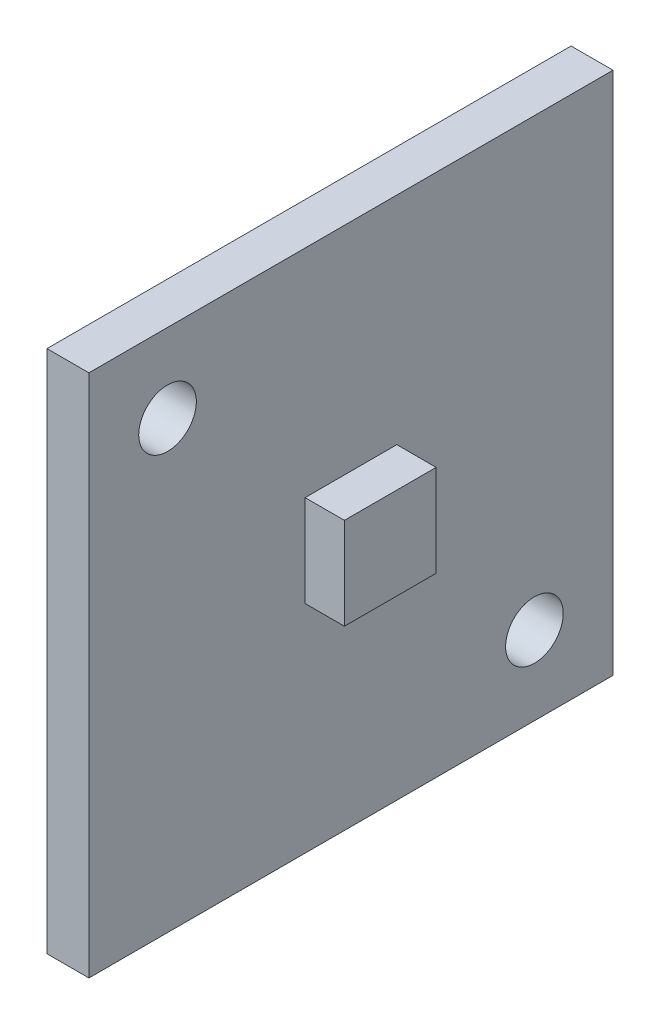
SolidWorks part; units mm, degrees
ref_plane "Front Plane" through (0, 0, 0) normal (0, 0, 1) x (1, 0, 0)
ref_plane "Top Plane" through (0, 0, 0) normal (0, 1, 0) x (1, 0, 0)
ref_plane "Right Plane" through (0, 0, 0) normal (1, 0, 0) x (0, 0, -1)
other "Configuration Table"
sketch "Sketch1" plane through (0, 0, 0) normal (1, 0, 0) x (0, 0, -1)
  line L1 (-10, -10) -> (10, -10)
  line L2 (-10, -10) -> (-10, 10)
  line L3 (-10, 10) -> (10, 10)
  line L4 (10, -10) -> (10, 10)
  line L5 (-10, -10) -> (10, 10) construction
  line L6 (-10, 10) -> (10, -10) construction
  point P6 (0, 0)
  dimension "D1" = 20
  dimension "D2" = 20
extrude "Board" add sketch "Sketch1" against normal blind 1.6
sketch "Sketch2" plane through (0, 0, 0) normal (1, 0, 0) x (0, 0, -1)
  line L0 (-1.75, -1.75) -> (1.75, -1.75)
  line L1 (1.75, -1.75) -> (1.75, 1.75)
  line L2 (1.75, 1.75) -> (-1.75, 1.75)
  line L3 (-1.75, 1.75) -> (-1.75, -1.75)
extrude "UV_LED_3535" add sketch "Sketch2" along normal blind 1.5
sketch "Sketch3" plane through (0, 0, 0) normal (1, 0, 0) x (0, 0, -1)
  circle A0 centre (7, -7) radius 1.1
  circle A1 centre (-7, 7) radius 1.1
  dimension "D1" = 2.2
  dimension "D2" = 2.2
extrude "Holes_M2" cut sketch "Sketch3" along normal through all and the other way through all
equation "\"Jar_OD\"= 90  'ASSUMED - Part G fallback - jar outer diameter"
equation "\"Jar_H\"= 120  'ASSUMED - Part G fallback - jar height"
equation "\"Pump_L\"= 45  'ASSUMED - Part G fallback"
equation "\"Pump_W\"= 24  'ASSUMED - Part G fallback"
equation "\"Pump_H\"= 33  'ASSUMED - Part G fallback"
equation "\"Pump_Outlet_OD\"= 7.5  'ASSUMED - Part G fallback"
equation "\"Tube_OD\"= 8  'ASSUMED - Part G fallback"
equation "\"Tube_ID\"= 6  'ASSUMED - Part G fallback"
equation "\"TDS_Body_Dia\"= 12  'ASSUMED - Part G fallback"
equation "\"TDS_Wet_Len\"= 45  'ASSUMED - Part G fallback - length in water"
equation "\"DS_Tube_Dia\"= 6  'ASSUMED - Part G fallback"
equation "\"DS_Tube_Len\"= 50  'ASSUMED - Part G fallback"
equation "\"ORP_Body_Dia\"= 12  'ASSUMED - Part G fallback"
equation "\"ORP_Body_Len\"= 150  'ASSUMED - Part G fallback"
equation "\"ORP_Cap_Dia\"= 16  'ASSUMED - Part G fallback"
equation "\"Turb_W\"= 33  'ASSUMED - Part G fallback - head width"
equation "\"Turb_D\"= 28  'ASSUMED - Part G fallback - head depth"
equation "\"Turb_H\"= 30  'ASSUMED - Part G fallback - head height"
equation "\"Turb_Slot_W\"= 10  'ASSUMED - Part G fallback - slot width"
equation "\"Flow_L\"= 62  'ASSUMED - Part G fallback YF-S201"
equation "\"Flow_W\"= 36  'ASSUMED - Part G fallback"
equation "\"Flow_H\"= 35  'ASSUMED - Part G fallback"
equation "\"Thread_G12_OD\"= 20.955  'ASSUMED - Part G fallback thread G1/2 (major diameter)"
equation "\"Valve_L\"= 75  'ASSUMED - Part G fallback"
equation "\"Valve_W\"= 45  'ASSUMED - Part G fallback"
equation "\"Valve_H\"= 60  'ASSUMED - Part G fallback"
equation "\"Tee_L\"= 40  'ASSUMED - Part G fallback - overall length"
equation "\"Tee_Branch_L\"= 25  'ASSUMED - Part G fallback"
equation "\"Tee_OD\"= 12  'ASSUMED - Part G fallback"
equation "\"Cuv_W\"= 12.5  'ASSUMED - old R3 cuvette (station suppressed in SS4)"
equation "\"Cuv_D\"= 12.5  'ASSUMED - old R3 cuvette (station suppressed in SS4)"
equation "\"Cuv_H\"= 45  'ASSUMED - old R3 cuvette (station suppressed in SS4)"
equation "\"LED_Board_L\"= 20  'ASSUMED - Part G fallback"
equation "\"LED_Board_W\"= 20  'ASSUMED - Part G fallback - LED at centre"
equation "\"GUVA_L\"= 20  'ASSUMED - Part G fallback"
equation "\"GUVA_W\"= 12  'ASSUMED - Part G fallback - sensor at centre"
equation "\"Reed_L\"= 27  'ASSUMED - Part G fallback MC-38 half"
equation "\"Reed_W\"= 14  'ASSUMED - Part G fallback"
equation "\"Reed_H\"= 8  'ASSUMED - Part G fallback"
equation "\"ESP_L\"= 51  'ASSUMED - Part G fallback"
equation "\"ESP_W\"= 28  'ASSUMED - Part G fallback"
equation "\"TFT_L\"= 58  'ASSUMED - Part G fallback - board"
equation "\"TFT_W\"= 35  'ASSUMED - Part G fallback - board"
equation "\"TFT_Win_L\"= 35  'ASSUMED - Part G fallback - visible window"
equation "\"TFT_Win_W\"= 28  'ASSUMED - Part G fallback - visible window"
equation "\"Relay_L\"= 50  'ASSUMED - Part G fallback"
equation "\"Relay_W\"= 26  'ASSUMED - Part G fallback"
equation "\"Relay_H\"= 19  'ASSUMED - Part G fallback"
equation "\"Mosfet_L\"= 34  'ASSUMED - Part G fallback"
equation "\"Mosfet_W\"= 17  'ASSUMED - Part G fallback"
equation "\"Mosfet_H\"= 12  'ASSUMED - Part G fallback"
equation "\"TDS_Board_L\"= 42  'ASSUMED - Part G fallback"
equation "\"TDS_Board_W\"= 32  'ASSUMED - Part G fallback"
equation "\"Turb_Board_L\"= 38  'ASSUMED - Part G fallback"
equation "\"Turb_Board_W\"= 28  'ASSUMED - Part G fallback"
equation "\"BNC_Thread_Dia\"= 9.5  'ASSUMED - Part G fallback"
equation "\"Plate_L\"= 420  'ASSUMED - Part G fallback"
equation "\"Plate_W\"= 297  'ASSUMED - Part G fallback"
equation "\"Plate_T\"= 6  'ASSUMED - Part G fallback"
equation "\"Probe_Clr\"= 0.3  'DESIGN VALUE - Part C rule 3 - printed probe hole = diameter + 0.3"
equation "\"Cuv_Clr\"= 0.2  'DESIGN VALUE - Part C rule 3 - cuvette pocket = size + 0.2"
equation "\"Label_H\"= 0.6  'DESIGN VALUE - Part D - raised label height"
equation "\"D1@Sketch1\" = \"LED_Board_W\""
equation "\"D2@Sketch1\" = \"LED_Board_L\""
equation "\"Booster_L\"= 150  'ASSUMED - Part G fallback - booster pump"
equation "\"Booster_W\"= 95  'ASSUMED - Part G fallback"
equation "\"Booster_H\"= 100  'ASSUMED - Part G fallback"
equation "\"PTube_OD\"= 6.35  'ASSUMED - Part G fallback - product tube 1/4 inch"
equation "\"Qz_Out\"= 12  'ASSUMED - Part G fallback - quartz channel outside square"
equation "\"Qz_Path\"= 10  'ASSUMED - Part G fallback - quartz channel inside light path"
equation "\"Qz_L\"= 40  'ASSUMED - Part G fallback - quartz channel length"
equation "\"LED860_Dia\"= 5  'ASSUMED - Part G fallback - 860 nm LED"
equation "\"BPW_L\"= 5.4  'ASSUMED - Part G fallback - BPW34"
equation "\"BPW_W\"= 4.3  'ASSUMED - Part G fallback - BPW34"
equation "\"Cart_Dia\"= 50  'ASSUMED - Part G fallback - sediment and pre-carbon cartridges"
equation "\"Cart_L\"= 255  'ASSUMED - Part G fallback"
equation "\"UF_Dia\"= 50  'ASSUMED - Part G fallback - UF cartridge"
equation "\"UF_L\"= 260  'ASSUMED - Part G fallback"
equation "\"RO_Dia\"= 62  'ASSUMED - Part G fallback - RO membrane housing"
equation "\"RO_L\"= 300  'ASSUMED - Part G fallback"
equation "\"UVC_Dia\"= 40  'ASSUMED - Part G fallback - UV-C chamber"
equation "\"UVC_L\"= 300  'ASSUMED - Part G fallback"
equation "\"Tank_W\"= 260  'ASSUMED - Part G fallback - storage tank"
equation "\"Tank_D\"= 160  'ASSUMED - Part G fallback"
equation "\"Tank_H\"= 300  'ASSUMED - Part G fallback"
equation "\"Cab_W\"= 400  'ASSUMED - Part G fallback - purifier cabinet"
equation "\"Cab_D\"= 270  'ASSUMED - Part G fallback"
equation "\"Cab_H\"= 560  'ASSUMED - Part G fallback"
equation "\"ORP_Board_L\"= 40  'ASSUMED - Part G fallback - ORP buffer board"
equation "\"ORP_Board_W\"= 30  'ASSUMED - Part G fallback"
equation "\"Opt_Board_L\"= 50  'ASSUMED - Part G fallback - optical front-end board"
equation "\"Opt_Board_W\"= 40  'ASSUMED - Part G fallback"
equation "\"Buck_L\"= 43  'ASSUMED - Part G fallback - 12 V to 5 V buck module"
equation "\"Buck_W\"= 21  'ASSUMED - Part G fallback"
equation "\"Buck_H\"= 14  'ASSUMED - Part G fallback"
equation "\"BB_L\"= 165  'ASSUMED - Part G fallback - breadboard (As_Built_R3 only)"
equation "\"BB_W\"= 55  'ASSUMED - Part G fallback"
equation "\"BB_H\"= 10  'ASSUMED - Part G fallback"
